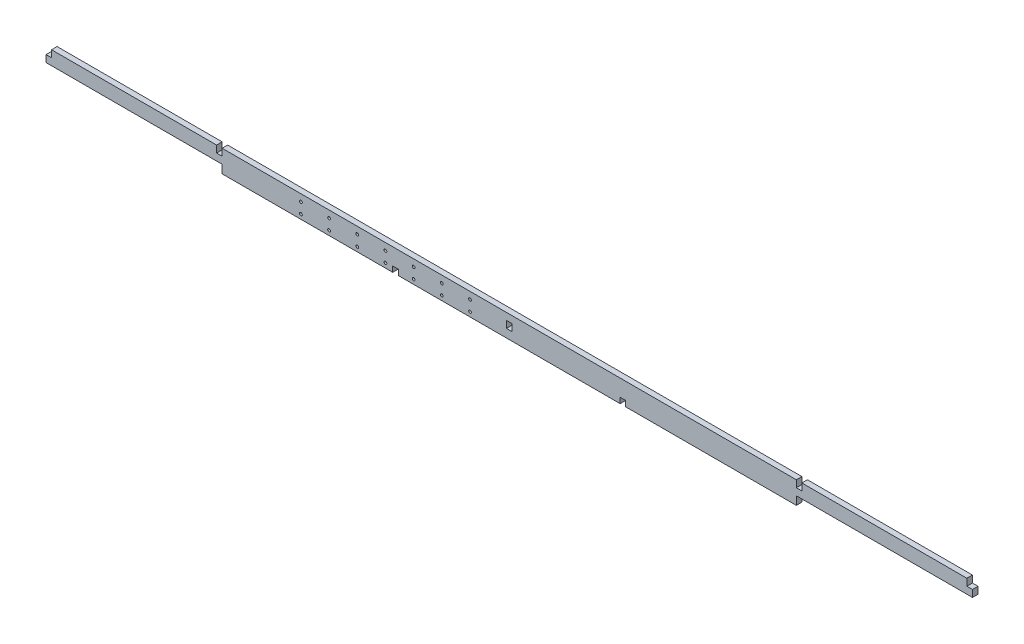
SolidWorks part; units mm, degrees
ref_plane "Front Plane" through (0, 0, 0) normal (0, 0, 1) x (1, 0, 0)
ref_plane "Top Plane" through (0, 0, 0) normal (0, 1, 0) x (1, 0, 0)
ref_plane "Right Plane" through (0, 0, 0) normal (1, 0, 0) x (0, 0, -1)
sketch "Sketch1" plane through (0, 0, 0) normal (0, 0, 1) x (1, 0, 0)
  line L0 (210, -10) -> (200, -10)
  line L1 (-210, 20) -> (210, 20)
  line L2 (-210, -10) -> (-210, -20)
  line L3 (-210, -20) -> (-5.05, -20)
  line L4 (210, -10) -> (210, -20)
  line L5 (-210, 20) -> (210, -20) construction
  line L6 (-210, -20) -> (210, 20) construction
  line L7 (200, -10) -> (200, 20) construction
  line L8 (0, 0) -> (0, -9.8972) construction
  line L9 (-210, -10) -> (-200, -10)
  line L10 (-200, -10) -> (-200, 20) construction
  line L11 (-200, -10) -> (-200, -20)
  line L12 (200, -10) -> (200, -20)
  line L16 (-5.05, -20) -> (210, -20)
  line L17 (-5, 7.5) -> (5, 7.5)
  line L19 (-5, 7.5) -> (5.05, 7.5)
  line L20 (-5, 7.5) -> (-5, -5)
  line L21 (-5, -5) -> (5.05, -5)
  line L22 (5.05, 7.5) -> (5.05, -5)
  line L23 (210, -20) -> (517.5, -20)
  line L24 (517.5, 20) -> (210, 20)
  line L25 (210, -10) -> (210, 20)
  line L26 (-517.5, 20) -> (-517.5, 7.5)
  line L27 (-210, -20) -> (-517.5, -20)
  line L28 (-517.5, 20) -> (-210, 20)
  line L29 (-527.5, -5) -> (-517.5, -5)
  line L31 (-517.5, 7.5) -> (-527.5, 7.5)
  line L32 (-517.5, -5) -> (-517.5, -20)
  line L33 (527.5, -5) -> (825, -5)
  line L34 (825, -5) -> (835, -5)
  line L35 (517.5, 7.5) -> (527.5, 7.5)
  line L36 (-517.5, 7.5) -> (-517.5, 20)
  line L37 (527.5, -5) -> (517.5, -5)
  line L38 (517.5, -5) -> (517.5, -20)
  line L39 (835, -5) -> (835, 7.5)
  line L40 (835, 7.5) -> (825, 7.5)
  line L41 (825, 7.5) -> (825, 20)
  line L42 (825, 20) -> (517.5, 20)
  line L43 (527.5, 7.5) -> (527.5, 20)
  line L44 (517.5, 7.5) -> (517.5, 20)
  line L45 (-527.5, 7.5) -> (-527.5, 20)
  line L46 (-835, 7.5) -> (-825, 7.5)
  line L47 (-835, -5) -> (-835, 7.5)
  line L48 (-825, -5) -> (-835, -5)
  line L49 (-825, 7.5) -> (-825, 20)
  line L50 (-825, 20) -> (-517.5, 20)
  line L51 (-527.5, -5) -> (-825, -5)
  point P0 (0, 0)
  point P19 (0, -9.8972)
  point P20 (0, -10)
  point P25 (0, 7.5)
  dimension "D1" = 40
  dimension "D2" = 420
  dimension "D3" = 10
  dimension "D4" = 10
  dimension "D6" = 0
  dimension "D7" = 297.5
  dimension "D8" = 10
  dimension "D9" = 0
  dimension "D10" = 12.5
  dimension "D11" = 12.5
  dimension "D12" = 12.5
  dimension "D13" = 10
  dimension "D14" = 12.5
  dimension "D15" = 12.5
  dimension "D16" = 10
extrude "Boss-Extrude1" add sketch "Sketch1" along normal blind 10
sketch "Sketch2" plane through (0, 0, 10) normal (0, 0, 1) x (1, 0, 0)
  line L0 (-400.9, -24.45) -> (-400.9, 20)
  line L1 (-517.5, 20) -> (-517.5, 7.5) construction
  line L3 (-397.1034, 20) -> (-397.1034, -24.45)
  line L4 (-517.5, 20) -> (-517.5, 7.5)
  line L5 (-502.5, 20) -> (-502.5, -20) construction
  line L6 (-517.5, 20) -> (517.5, 20) construction
  line L7 (-210, -20) -> (-517.5, -20) construction
  line L8 (-58, 20) -> (-502.5, 20)
  line L9 (-502.5, -0.32) -> (-483.4419, -2.1147)
  line L10 (-400.9, -24.45) -> (-58, -24.45)
  line L11 (-58, -24.45) -> (-58, 20)
  arc A2 (-502.5, 20) -> (-502.5, -0.32) centre (-502.5, 9.84) ccw
  circle A16 centre (-70.7, -11.75) radius 2.5
  circle A17 centre (-70.7, 7.3) radius 2.5
  circle A18 centre (-121.5, 7.3) radius 2.5
  circle A19 centre (-121.5, -11.75) radius 2.5
  circle A20 centre (-172.3, -11.75) radius 2.5
  circle A21 centre (-172.3, 7.3) radius 2.5
  circle A22 centre (-223.1, 7.3) radius 2.5
  circle A23 centre (-223.1, -11.75) radius 2.5
  circle A24 centre (-273.9, -11.75) radius 2.5
  circle A25 centre (-273.9, 7.3) radius 2.5
  circle A26 centre (-324.7, 7.3) radius 2.5
  circle A27 centre (-375.5, 7.3) radius 2.5
  circle A28 centre (-324.7, -11.75) radius 2.5
  circle A29 centre (-375.5, -11.75) radius 2.5
  spline S2 degree 3 poles (-483.4419, -2.1147) (-467.316, -3.6333) (-415.8483, -10.8728) (-419.8044, -24.45) (-400.9, -24.45) knots 0 0 0 0 0.266939 0.794936 0.794936 0.794936 0.794936
  dimension "D1" = 15
extrude "Cut-Extrude1" cut sketch "Sketch2" against normal through all contours A27 | A29 | A28 | A26 | A25 | A24 | A23 | A22 | A21 | A19 | A18 | A17 | A16 | A20
